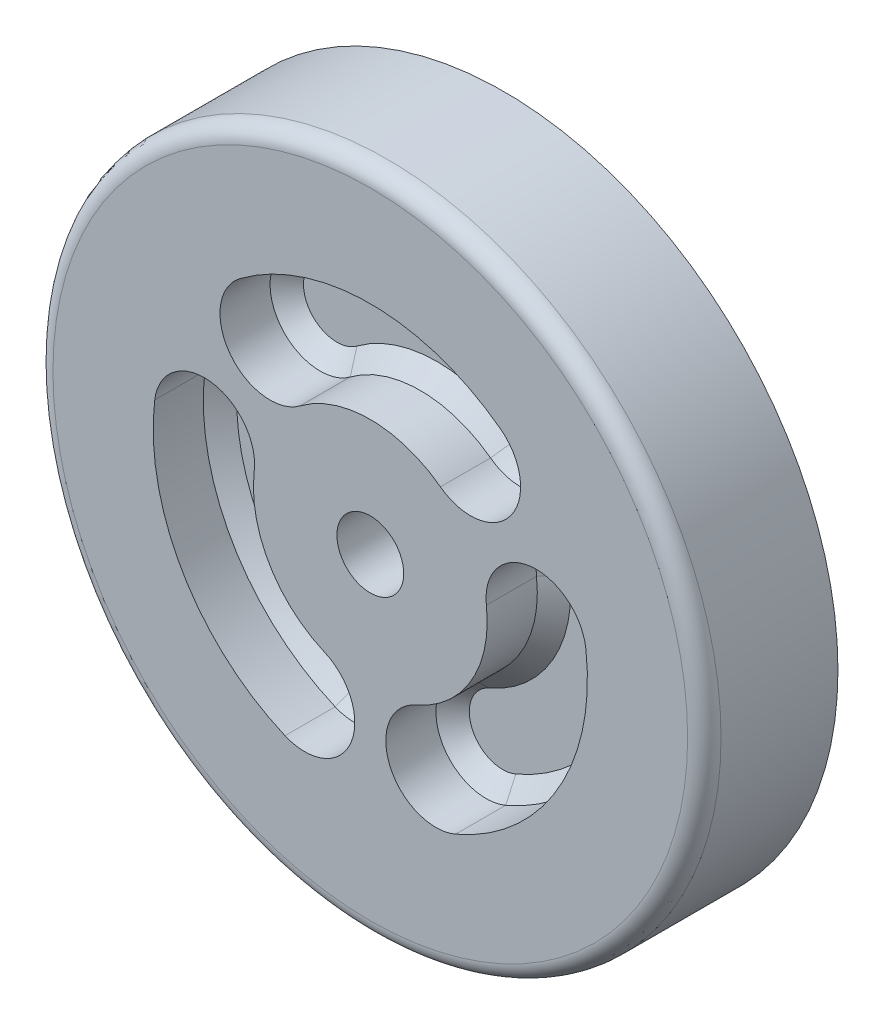
SolidWorks part; units mm, degrees
ref_plane "Front Plane" through (0, 0, 0) normal (0, 0, 1) x (1, 0, 0)
ref_plane "Top Plane" through (0, 0, 0) normal (0, 1, 0) x (1, 0, 0)
ref_plane "Right Plane" through (0, 0, 0) normal (1, 0, 0) x (0, 0, -1)
sketch "Sketch1" plane through (0, 0, 0) normal (0, 0, 1) x (1, 0, 0)
  circle A0 centre (0, 0) radius 100
  dimension "D1" = 200
extrude "Boss-Extrude1" add sketch "Sketch1" along normal blind 40
sketch "Sketch5" plane through (0, 0, 40) normal (0, 0, 1) x (1, 0, 0)
  arc A0 (-30, 40) -> (30, 40) centre (0, 0) cw construction
  arc A1 (39, 52) -> (-39, 52) centre (0, 0) ccw
  arc A2 (21, 28) -> (-21, 28) centre (0, 0) ccw
  arc A3 (21, 28) -> (39, 52) centre (30, 40) ccw
  arc A4 (-39, 52) -> (-21, 28) centre (-30, 40) ccw
  circle A5 centre (0, 0) radius 50 construction
  arc A6 (49.641, 5.9808) -> (19.641, -45.9808) centre (0, 0) cw construction
  arc A7 (25.5333, -59.775) -> (64.5333, 7.775) centre (0, 0) ccw
  arc A8 (13.7487, -32.1865) -> (34.7487, 4.1865) centre (0, 0) ccw
  arc A9 (13.7487, -32.1865) -> (25.5333, -59.775) centre (19.641, -45.9808) ccw
  arc A10 (64.5333, 7.775) -> (34.7487, 4.1865) centre (49.641, 5.9808) ccw
  arc A11 (-19.641, -45.9808) -> (-49.641, 5.9808) centre (0, 0) cw construction
  arc A12 (-64.5333, 7.775) -> (-25.5333, -59.775) centre (0, 0) ccw
  arc A13 (-34.7487, 4.1865) -> (-13.7487, -32.1865) centre (0, 0) ccw
  arc A14 (-34.7487, 4.1865) -> (-64.5333, 7.775) centre (-49.641, 5.9808) ccw
  arc A15 (-25.5333, -59.775) -> (-13.7487, -32.1865) centre (-19.641, -45.9808) ccw
  point P4 (0, 50)
  point P13 (43.3013, -25)
  point P17 (0, 35)
  point P23 (-43.3013, -25)
  point P28 (0, 0)
  dimension "D1" = 50
  dimension "D2" = 15
  dimension "D3" = 40
  dimension "D4" = 3
extrude "Cut-Extrude2" cut sketch "Sketch5" against normal blind 20
fillet "Fillet1" radius 5 1 edges at (100, 0, 40)
chamfer "Chamfer1" distance 5 angle 45 12 edges at (-30.3109, -17.5, 20) (-5.8468, -51.8731, 20) (-56.2917, -32.5, 20) (-47.8468, 20.8731, 20) (30.3109, -17.5, 20) (47.8468, 20.8731, 20) (56.2917, -32.5, 20) (5.8468, -51.8731, 20) (0, 35, 20) (-42, 31, 20) (0, 65, 20) (42, 31, 20)
sketch "Sketch6" plane through (0, 0, 40) normal (0, 0, 1) x (1, 0, 0)
  circle A0 centre (0, 0) radius 10
  dimension "D1" = 20
extrude "Cut-Extrude3" cut sketch "Sketch6" against normal through all
